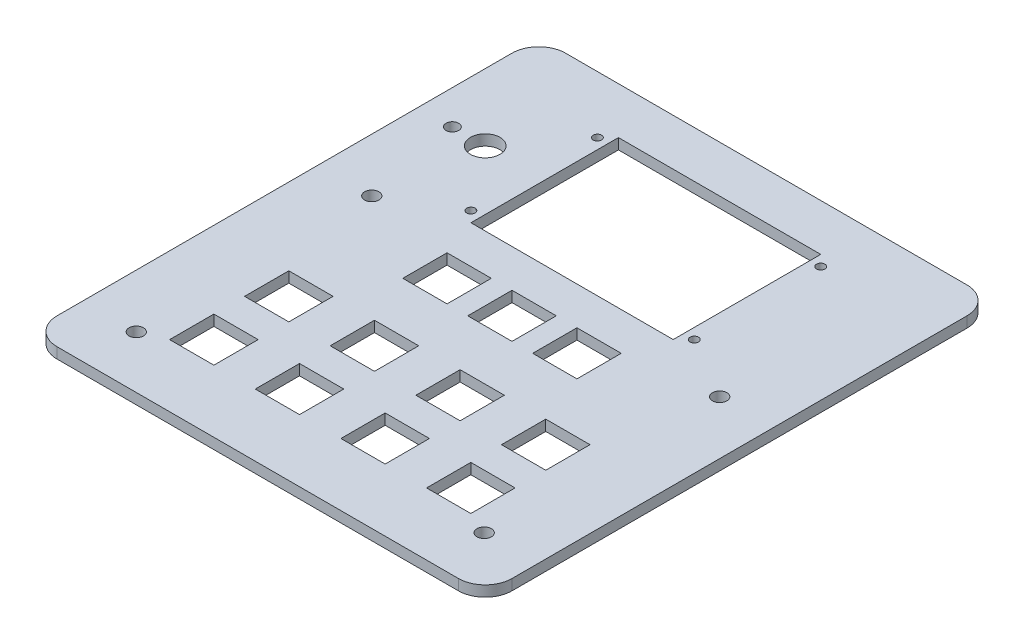
SolidWorks part; units mm, degrees
ref_plane "Front Plane" through (0, 0, 0) normal (0, 0, 1) x (1, 0, 0)
ref_plane "Top Plane" through (0, 0, 0) normal (0, 1, 0) x (1, 0, 0)
ref_plane "Right Plane" through (0, 0, 0) normal (1, 0, 0) x (0, 0, -1)
sketch "Sketch1" plane through (0, 0, 0) normal (0, 1, 0) x (1, 0, 0)
  line L0 (0, -55) -> (0, 55) construction
  line L1 (-53.975, -60.325) -> (53.975, -60.325)
  line L2 (-53.975, -60.325) -> (-53.975, 60.325)
  line L3 (-53.975, 60.325) -> (53.975, 60.325)
  line L4 (53.975, -60.325) -> (53.975, 60.325)
  line L5 (-53.975, -60.325) -> (53.975, 60.325) construction
  line L6 (-53.975, 60.325) -> (53.975, -60.325) construction
  line L7 (-24, 14.25) -> (24, 14.25)
  line L8 (-24, 14.25) -> (-24, 49.25)
  line L9 (-24, 49.25) -> (24, 49.25)
  line L10 (24, 14.25) -> (24, 49.25)
  line L11 (-24, 14.25) -> (24, 49.25) construction
  line L12 (-24, 49.25) -> (24, 14.25) construction
  line L13 (25.23, -45.5029) -> (35.73, -45.5029)
  line L14 (-30.48, -31.3629) -> (30.48, -31.3629) construction
  line L15 (-30.48, -31.3629) -> (-30.48, -22.4729) construction
  line L16 (-30.48, -22.4729) -> (30.48, -22.4729) construction
  line L17 (30.48, -31.3629) -> (30.48, -22.4729) construction
  line L18 (-30.48, -31.3629) -> (30.48, -22.4729) construction
  line L19 (-30.48, -22.4729) -> (30.48, -31.3629) construction
  line L20 (-35.73, -27.7229) -> (-25.23, -27.7229)
  line L21 (-35.73, -27.7229) -> (-35.73, -17.2229)
  line L22 (-35.73, -17.2229) -> (-25.23, -17.2229)
  line L23 (-25.23, -27.7229) -> (-25.23, -17.2229)
  line L24 (-35.73, -27.7229) -> (-25.23, -17.2229) construction
  line L25 (-35.73, -17.2229) -> (-25.23, -27.7229) construction
  line L26 (-15.41, -27.7229) -> (-4.91, -27.7229)
  line L27 (-15.41, -27.7229) -> (-15.41, -17.2229)
  line L28 (-15.41, -17.2229) -> (-4.91, -17.2229)
  line L29 (-4.91, -27.7229) -> (-4.91, -17.2229)
  line L30 (-15.41, -27.7229) -> (-4.91, -17.2229) construction
  line L31 (-15.41, -17.2229) -> (-4.91, -27.7229) construction
  line L32 (4.91, -27.7229) -> (15.41, -27.7229)
  line L33 (4.91, -27.7229) -> (4.91, -17.2229)
  line L34 (4.91, -17.2229) -> (15.41, -17.2229)
  line L35 (15.41, -27.7229) -> (15.41, -17.2229)
  line L36 (4.91, -27.7229) -> (15.41, -17.2229) construction
  line L37 (4.91, -17.2229) -> (15.41, -27.7229) construction
  line L38 (25.23, -27.7229) -> (35.73, -27.7229)
  line L39 (25.23, -27.7229) -> (25.23, -17.2229)
  line L40 (25.23, -17.2229) -> (35.73, -17.2229)
  line L41 (35.73, -27.7229) -> (35.73, -17.2229)
  line L42 (25.23, -27.7229) -> (35.73, -17.2229) construction
  line L43 (25.23, -17.2229) -> (35.73, -27.7229) construction
  line L44 (35.73, -35.0029) -> (35.73, -45.5029)
  line L45 (25.23, -35.0029) -> (35.73, -35.0029)
  line L46 (25.23, -35.0029) -> (25.23, -45.5029)
  line L47 (4.91, -35.0029) -> (15.41, -35.0029)
  line L48 (15.41, -35.0029) -> (15.41, -45.5029)
  line L49 (4.91, -45.5029) -> (15.41, -45.5029)
  line L50 (4.91, -35.0029) -> (4.91, -45.5029)
  line L51 (-4.91, -35.0029) -> (-4.91, -45.5029)
  line L52 (-15.41, -45.5029) -> (-4.91, -45.5029)
  line L53 (-15.41, -35.0029) -> (-15.41, -45.5029)
  line L54 (-15.41, -35.0029) -> (-4.91, -35.0029)
  line L55 (-35.73, -35.0029) -> (-25.23, -35.0029)
  line L56 (-25.23, -35.0029) -> (-25.23, -45.5029)
  line L57 (-35.73, -45.5029) -> (-25.23, -45.5029)
  line L58 (-35.73, -35.0029) -> (-35.73, -45.5029)
  line L59 (-53.975, 31.75) -> (53.975, 31.75) construction
  line L60 (0, 0) -> (0, -22.4729) construction
  line L65 (-41.275, -47.8729) -> (41.275, -47.8729) construction
  line L66 (-41.275, -47.8729) -> (-41.275, 8.0071) construction
  line L70 (-41.275, 8.0071) -> (41.275, 8.0071) construction
  line L71 (41.275, -47.8729) -> (41.275, 8.0071) construction
  line L76 (-26.5, 16.75) -> (26.5, 16.75) construction
  line L77 (-26.5, 16.75) -> (-26.5, 46.75) construction
  line L78 (-26.5, 46.75) -> (26.5, 46.75) construction
  line L79 (26.5, 16.75) -> (26.5, 46.75) construction
  line L80 (-26.5, 16.75) -> (26.5, 46.75) construction
  line L81 (-26.5, 46.75) -> (26.5, 16.75) construction
  line L82 (-5.25, -5.25) -> (5.25, -5.25)
  line L83 (-5.25, -5.25) -> (-5.25, 5.25)
  line L84 (-5.25, 5.25) -> (5.25, 5.25)
  line L85 (5.25, -5.25) -> (5.25, 5.25)
  line L86 (-5.25, -5.25) -> (5.25, 5.25) construction
  line L87 (-5.25, 5.25) -> (5.25, -5.25) construction
  line L93 (-15.41, 5.25) -> (-5.25, 5.25) construction
  line L95 (-15.41, -5.25) -> (-15.41, 5.25) construction
  line L96 (15.41, 5.25) -> (15.41, -5.25) construction
  line L97 (-41.275, -47.8729) -> (41.275, 8.0071) construction
  line L98 (-41.275, 8.0071) -> (41.275, -47.8729) construction
  line L99 (0, 0) -> (-15.41, 0) construction
  line L100 (0, 0) -> (15.41, 0) construction
  line L101 (-20.66, -5.25) -> (-10.16, -5.25)
  line L102 (-20.66, -5.25) -> (-20.66, 5.25)
  line L103 (-20.66, 5.25) -> (-10.16, 5.25)
  line L104 (-10.16, -5.25) -> (-10.16, 5.25)
  line L105 (-20.66, -5.25) -> (-10.16, 5.25) construction
  line L106 (-20.66, 5.25) -> (-10.16, -5.25) construction
  line L108 (10.16, -5.25) -> (20.66, -5.25)
  line L109 (10.16, -5.25) -> (10.16, 5.25)
  line L110 (10.16, 5.25) -> (20.66, 5.25)
  line L111 (20.66, -5.25) -> (20.66, 5.25)
  line L112 (10.16, -5.25) -> (20.66, 5.25) construction
  line L113 (10.16, 5.25) -> (20.66, -5.25) construction
  circle A0 centre (-38.1, 31.75) radius 3.5
  circle A1 centre (-26.5, 46.75) radius 1
  circle A2 centre (26.5, 46.75) radius 1
  circle A3 centre (26.5, 16.75) radius 1
  circle A4 centre (-26.5, 16.75) radius 1
  circle A5 centre (-45.9, 31.75) radius 1.5
  circle A6 centre (-41.275, 8.0071) radius 1.7
  circle A7 centre (41.275, 8.0071) radius 1.7
  circle A8 centre (41.275, -47.8729) radius 1.7
  circle A9 centre (-41.275, -47.8729) radius 1.7
  point P0 (0, 0)
  point P6 (0, 31.75)
  point P13 (0, -26.9179)
  point P20 (-10.16, -22.4729)
  point P29 (10.16, -22.4729)
  point P38 (0, -19.9329)
  point P58 (0, 31.75)
  point P61 (38.1, 31.75)
  point P69 (0, 31.75)
  point P80 (0, 0)
  dimension "D3" = 7
  dimension "D17" = 2
  dimension "D18" = 3
  dimension "D22" = 3.4
  dimension "D1" = 48
  dimension "D2" = 35
  dimension "D4" = 31.75
  dimension "D5" = 120.65
  dimension "D6" = 107.95
  dimension "D7" = 10.5
  dimension "D8" = 60.96
  dimension "D9" = 20.32
  dimension "D10" = 20.32
  dimension "D11" = 8.89
  dimension "D12" = 38.1
  dimension "D13" = 2.54
  dimension "D14" = 55.88
  dimension "D15" = 53
  dimension "D16" = 30
  dimension "D19" = 7.8
  dimension "D20" = 15.41
  dimension "D21" = 82.55
  dimension "D23" = 22.4729
extrude "Boss-Extrude1" add sketch "Sketch1" along normal blind 2.54
fillet "Fillet1" radius 6.35 4 edges at (-53.975, 1.27, -60.325) (-53.975, 1.27, 60.325) (53.975, 1.27, 60.325) (53.975, 1.27, -60.325)
